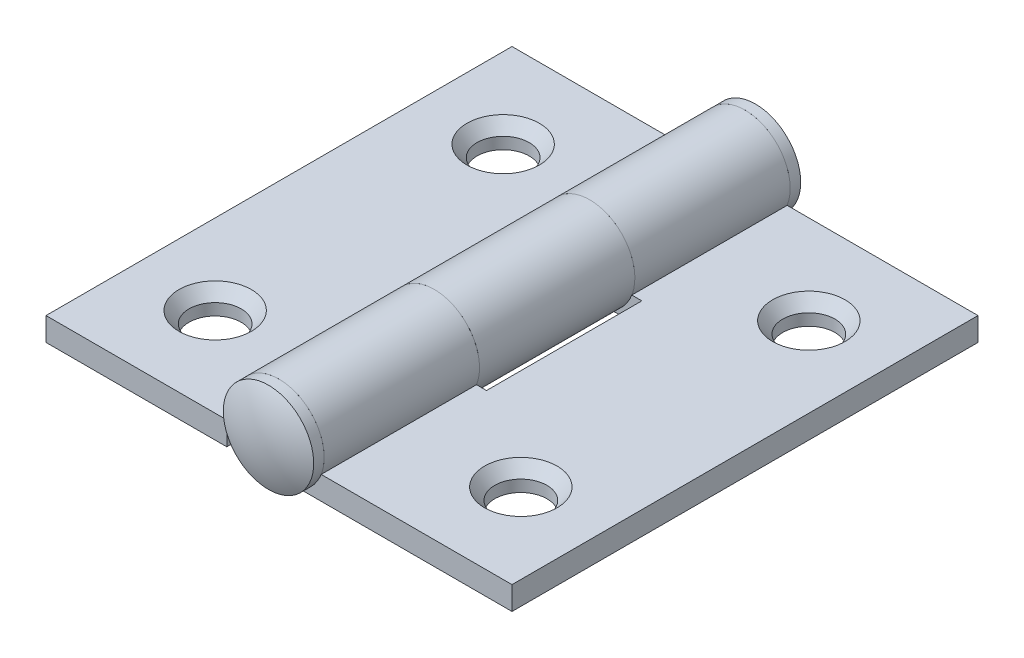
SolidWorks part; units mm, degrees
ref_plane "Front Plane" through (0, 0, 0) normal (0, 0, 1) x (1, 0, 0)
ref_plane "Top Plane" through (0, 0, 0) normal (0, 1, 0) x (1, 0, 0)
ref_plane "Right Plane" through (0, 0, 0) normal (1, 0, 0) x (0, 0, -1)
sketch "Sketch1" plane through (0, 0, 0) normal (0, 0, 1) x (1, 0, 0)
  line L0 (12.7, -2.157) -> (1.1906, -2.157)
  line L1 (12.7, -2.157) -> (12.7, -0.887)
  line L2 (12.7, -0.887) -> (2.2986, -0.887)
  line L3 (1.1906, -2.157) -> (1.1906, 0) construction
  line L4 (-2.4638, 0) -> (-2.4638, -2.157) construction
  line L5 (-12.7, -0.887) -> (-2.8448, -0.887)
  line L6 (-12.7, -0.887) -> (-12.7, -2.157)
  line L7 (-12.7, -2.157) -> (-2.8448, -2.157)
  line L8 (-2.8448, -0.887) -> (-2.8448, -2.157)
  circle A0 centre (0, 0) radius 1.1906
  arc A1 (1.1906, -2.157) -> (2.2986, -0.887) centre (0, 0) cw
  point P5 (-1.1906, 0)
  dimension "D3" = 0.381
  dimension "knuckle dia" = 4.9276
  dimension "Wd" = 25.4
  dimension "D4" = 12.7
extrude "Extrude1" add sketch "Sketch1" along normal mid plane 25.4
sketch "Sketch2" plane through (0, -0.887, 0) normal (0, 1, 0) x (1, 0, 0)
  line L1 (-2.8448, -7.62) -> (2.8448, -7.62)
  line L2 (-2.8448, -7.62) -> (-2.8448, -12.7)
  line L3 (-2.8448, -12.7) -> (2.8448, -12.7)
  line L4 (2.8448, -7.62) -> (2.8448, -12.7)
  line L5 (-2.8448, -2.54) -> (2.8448, -2.54)
  line L6 (-2.8448, -2.54) -> (-2.8448, 2.54)
  line L7 (-2.8448, 2.54) -> (2.8448, 2.54)
  line L8 (2.8448, -2.54) -> (2.8448, 2.54)
  line L9 (-2.8448, 12.7) -> (2.8448, 12.7)
  line L10 (-2.8448, 12.7) -> (-2.8448, 7.62)
  line L11 (-2.8448, 7.62) -> (2.8448, 7.62)
  line L12 (2.8448, 12.7) -> (2.8448, 7.62)
  line L14 (2.4638, 12.7) -> (-2.4638, 12.7) construction
  line L17 (-2.4638, -12.7) -> (2.4638, -12.7) construction
  line L18 (-2.8448, 0) -> (2.8448, 0) construction
  line L19 (12.7, 12.7) -> (2.2986, 12.7) construction
  line L20 (2.4638, -12.7) -> (2.4638, 12.7) construction
  line L21 (-2.8448, 12.7) -> (-12.7, 12.7) construction
  line L22 (-2.4638, 12.7) -> (-2.4638, -12.7) construction
  dimension "D1" = 5.08
  dimension "D2" = 0.381
  dimension "D3" = 0.381
sketch "Sketch6" plane through (0, 0, 0) normal (0, 1, 0) x (1, 0, 0)
  line L0 (-2.4638, -12.7) -> (-2.4638, -13.2715)
  line L1 (-2.4638, 12.7) -> (-1.1906, 12.7)
  line L2 (-1.1906, -12.7) -> (-2.4638, -12.7)
  line L3 (0, 0) -> (0, 12.7) construction
  line L4 (-2.8448, 12.7) -> (-12.7, 12.7) construction
  line L5 (-2.8448, -12.7) -> (-12.7, -12.7) construction
  line L6 (-2.4638, 13.2715) -> (-2.4638, 12.7)
  line L7 (0, 0) -> (6.3351, 0) construction
  line L10 (-1.1906, -12.7) -> (-1.1906, 12.7)
  line L11 (0, 13.843) -> (0, -13.843)
  arc A0 (-2.4638, 13.2715) -> (0, 13.843) centre (0, 8.2464) cw
  arc A1 (-2.4638, -13.2715) -> (0, -13.843) centre (0, -8.2464) ccw
  circle A2 centre (0, 13.2715) radius 0.5715 construction
  dimension "D2" = 1.143
revolve "Revolve1" add sketch "Sketch6" angle 360 about L11
sketch "Sketch20" plane through (0, -0.887, 0) normal (0, 1, 0) x (1, 0, 0)
  line L0 (-8.3312, 7.8486) -> (-8.3312, -7.8486) construction
  circle A0 centre (-8.3312, 7.8486) radius 1.4224
  circle A1 centre (-8.3312, -7.8486) radius 1.4224
  point P4 (-8.3312, 0)
  dimension "hole dia" = 2.8448
  dimension "side to side" = 8.3312
  dimension "top to bottom" = 15.6972
extrude "Extrude24" cut sketch "Sketch20" against normal through all
chamfer "Chamfer2" distance 0.635 angle 41 2 edges at (-8.3312, -0.887, 9.271) (-8.3312, -0.887, -6.4262)
mirror "Mirror2" about plane through (0, 0, 0) normal (1, 0, 0) of "Chamfer2", "Extrude24"
sketch "Sketch23" [suppressed] plane through (0, -1.376, 0) normal (0, 1, 0) x (1, 0, 0)
  line L0 (-19.4564, 0) -> (0, 0) construction
  circle A0 centre (-19.4564, 0) radius 1.7526
  circle A1 centre (-16.637, 29.718) radius 1.7526 construction
  dimension "side to side B" = 19.05
extrude "Extrude25" [suppressed] cut sketch "Sketch23" against normal through all
chamfer "Chamfer3" [suppressed] distance 0.635 angle 41
mirror "Mirror3" [suppressed] about plane through (0, 0, 0) normal (1, 0, 0)
sketch "Sketch8" plane through (0, 0, 0) normal (0, 1, 0) x (1, 0, 0)
  line L0 (-2.8448, 0) -> (2.8448, 0) construction
  line L1 (-2.8448, 4.2333) -> (2.8448, 4.2333)
  line L2 (-2.8448, 4.2333) -> (-2.8448, -4.2333)
  line L3 (-2.8448, -4.2333) -> (2.8448, -4.2333)
  line L4 (2.8448, 4.2333) -> (2.8448, -4.2333)
  line L5 (-2.8448, -12.7) -> (-2.8448, 12.7) construction
  line L6 (0, 4.2333) -> (0, 12.7) construction
  line L7 (2.4638, 12.7) -> (-2.4638, 12.7) construction
extrude "Extrude4" cut sketch "Sketch8" against normal through all and the other way through all
sketch "Sketch9" plane through (0, 0, -4.2333) normal (0, 0, 1) x (1, 0, 0)
  line L0 (-2.2986, -0.887) -> (-2.8448, -0.887)
  line L1 (-2.8448, -0.887) -> (-2.8448, -2.157)
  line L2 (-2.8448, -2.157) -> (-1.1906, -2.157)
  line L3 (-2.8448, -2.157) -> (-2.8448, -0.887) construction
  line L4 (-2.8448, -0.887) -> (-12.7, -0.887) construction
  line L5 (-12.7, -2.157) -> (-2.8448, -2.157) construction
  arc A0 (2.2986, -0.887) -> (1.1906, -2.157) centre (0, 0) ccw construction
  circle A1 centre (0, 0) radius 1.1906 construction
  arc A2 (-1.1906, -2.157) -> (-2.2986, -0.887) centre (0, 0) ccw
  circle A3 centre (0, 0) radius 1.1906
extrude "Extrude5" add sketch "Sketch9" along normal up to surface (8.4667 mm away) up to face at (1.1906, 0, 4.2333)
sketch "Sketch3" [suppressed] plane through (0, 0, 0) normal (0, 1, 0) x (1, 0, 0)
  line L0 (0, 7.62) -> (0, -7.62) construction
  line L1 (-3.937, 22.86) -> (3.937, 22.86)
  line L2 (-3.937, 22.86) -> (-3.937, 7.62)
  line L3 (-3.937, 7.62) -> (3.937, 7.62)
  line L4 (3.937, 22.86) -> (3.937, 7.62)
  line L5 (-3.937, -7.62) -> (3.937, -7.62)
  line L6 (-3.937, -7.62) -> (-3.937, -22.86)
  line L7 (-3.937, -22.86) -> (3.937, -22.86)
  line L8 (3.937, -7.62) -> (3.937, -22.86)
  line L9 (0, 22.86) -> (0, 38.1) construction
  line L11 (0, -22.86) -> (0, -38.1) construction
  line L13 (-3.937, -38.1) -> (-3.937, 38.1) construction
  line L14 (3.556, 38.1) -> (-3.556, 38.1) construction
extrude "Cut-Extrude1" [suppressed] cut sketch "Sketch3" against normal mid plane 76.2
sketch "Sketch4" [suppressed] plane through (0, 0, -22.86) normal (0, 0, 1) x (1, 0, 0)
  line L0 (-25.4, -2.9508) -> (-3.937, -2.9508) construction
  line L2 (-3.937, -1.376) -> (-3.279, -1.376)
  line L3 (-3.937, -1.376) -> (-3.937, -2.9508)
  line L4 (-3.937, -2.9508) -> (-1.9844, -2.9508)
  circle A0 centre (0, 0) radius 1.9844 construction
  circle A1 centre (0, 0) radius 1.9844
  arc A2 (3.279, -1.376) -> (1.9844, -2.9508) centre (0, 0) ccw construction
  arc A3 (-1.9844, -2.9508) -> (-3.279, -1.376) centre (0, 0) ccw
extrude "Extrude2" [suppressed] add sketch "Sketch4" along normal up to vertex
sketch "Sketch5" [suppressed] plane through (0, 0, 7.62) normal (0, 0, 1) x (1, 0, 0)
  line L3 (-3.279, -1.376) -> (-3.937, -1.376)
  line L4 (-3.937, -2.9508) -> (-1.9844, -2.9508)
  line L5 (-3.937, -1.376) -> (-3.937, -2.9508)
  line L6 (-3.279, -1.376) -> (-3.937, -1.376)
  line L7 (-3.937, -2.9508) -> (-1.9844, -2.9508)
  line L8 (-3.937, -1.376) -> (-3.937, -2.9508)
  circle A1 centre (0, 0) radius 1.9844
  circle A2 centre (0, 0) radius 1.9844
  arc A3 (-1.9844, -2.9508) -> (-3.279, -1.376) centre (0, 0) ccw
  arc A4 (-1.9844, -2.9508) -> (-3.279, -1.376) centre (0, 0) ccw
  dimension "D1" = 0
  dimension "D2" = 0
extrude "Extrude3" [suppressed] add sketch "Sketch5" along normal up to vertex
sketch "Sketch19" [suppressed] plane through (0, 0, 0) normal (0, 1, 0) x (1, 0, 0)
  line L1 (-12.7, -12.7) -> (12.7, -12.7)
  line L2 (-12.7, -12.7) -> (-12.7, -13.843)
  line L3 (-12.7, -13.843) -> (12.7, -13.843)
  line L4 (12.7, -12.7) -> (12.7, -13.843)
extrude "Extrude23" [suppressed] cut sketch "Sketch19" against normal through all and the other way through all
chamfer "Chamfer1" [suppressed] distance 0.5953 angle 45
sketch "Sketch21" plane through (0, 0, 0) normal (0, 1, 0) x (1, 0, 0)
  line L0 (-12.7, -12.7) -> (12.7, -12.7) construction
  point P4 (0, -12.7)
equation "\"D1@Sketch2\" = \"Leaf Ht@Extrude1\"/5"
equation "\"D4@Sketch1\" = \"Wd@Sketch1\"/2"
equation "\"D2@Sketch6\" = \"Leaf thick@Sketch1\"*.9"
equation "\"D1@Chamfer1\" = \"Pin Dia@Sketch1\" * .25"
equation "\"D1@Chamfer2\" = \"Leaf thick@Sketch1\" * .5"
equation "\"D1@Chamfer3\" = \"D1@Chamfer2\""
equation "\"D2@Chamfer3\" = \"D2@Chamfer2\""
